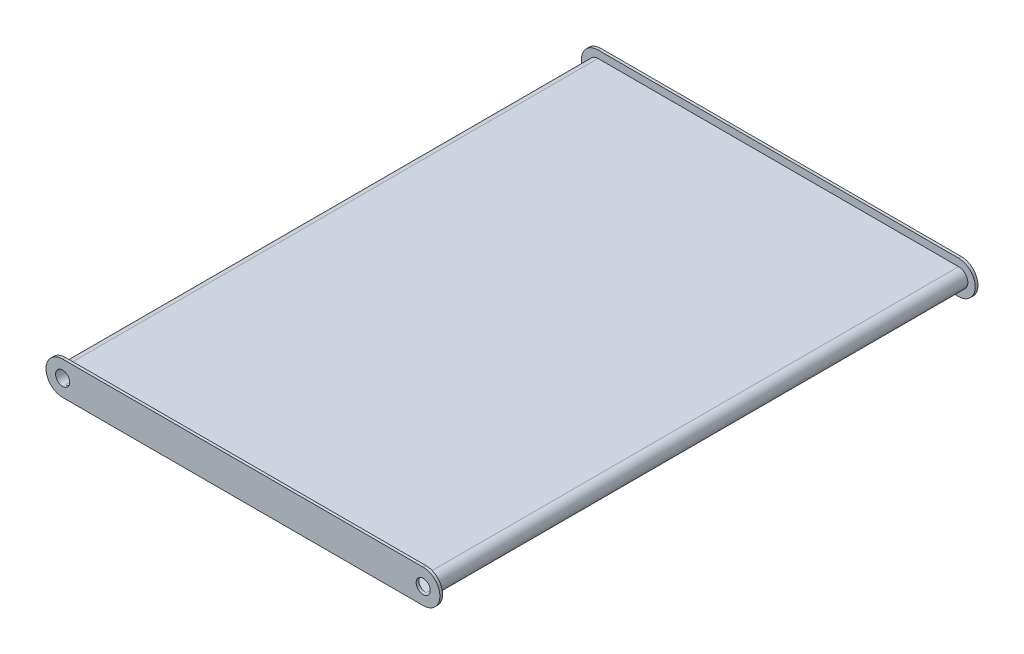
SolidWorks part; units mm, degrees
material "AISI 4130 Steel, annealed at 865C"
ref_plane "Front Plane" through (0, 0, 0) normal (0, 0, 1) x (1, 0, 0)
ref_plane "Top Plane" through (0, 0, 0) normal (0, 1, 0) x (1, 0, 0)
ref_plane "Right Plane" through (0, 0, 0) normal (1, 0, 0) x (0, 0, -1)
sketch "Sketch1" plane through (0, 0, 0) normal (0, 0, 1) x (1, 0, 0)
  line L0 (-324.9668, 0) -> (324.9668, 0) construction
  line L1 (-324.9668, 12.7) -> (324.9668, 12.7)
  line L2 (-324.9668, -12.7) -> (324.9668, -12.7)
  line L3 (-324.9668, 16.7) -> (324.9668, 16.7)
  line L4 (-324.9668, -16.7) -> (324.9668, -16.7)
  arc A0 (-324.9668, 12.7) -> (-324.9668, -12.7) centre (-324.9668, 0) ccw
  arc A1 (324.9668, -12.7) -> (324.9668, 12.7) centre (324.9668, 0) ccw
  arc A2 (324.9668, -16.7) -> (324.9668, 16.7) centre (324.9668, 0) ccw
  arc A3 (-324.9668, 16.7) -> (-324.9668, -16.7) centre (-324.9668, 0) ccw
  point P3 (0, 0)
  dimension "D2" = 12.7
  dimension "D1" = 649.9336
  dimension "D3" = 4
extrude "Boss-Extrude1" add sketch "Sketch1" along normal blind 960
sketch "Sketch2" plane through (0, 0, 960) normal (0, 0, 1) x (1, 0, 0)
  line L0 (-324.9668, 0) -> (324.9668, 0) construction
  line L1 (-324.9668, 30) -> (324.9668, 30)
  line L2 (-324.9668, -16.7) -> (324.9668, -16.7)
  line L3 (324.9668, 16.7) -> (-324.9668, 16.7)
  line L5 (324.9668, 16.7) -> (-324.9668, 16.7)
  line L6 (-324.9668, -30) -> (324.9668, -30)
  arc A0 (-324.9668, 30) -> (-324.9668, -30) centre (-324.9668, 0) ccw
  arc A1 (324.9668, -30) -> (324.9668, 30) centre (324.9668, 0) ccw
  arc A2 (-324.9668, 16.7) -> (-324.9668, -16.7) centre (-324.9668, 0) ccw
  arc A3 (324.9668, -16.7) -> (324.9668, 16.7) centre (324.9668, 0) ccw
  circle A6 centre (324.9668, 0) radius 12.7
  circle A7 centre (-324.9668, 0) radius 12.7
  point P0 (0, 0)
  dimension "D2" = 30
  dimension "D3" = 25.4
  dimension "D4" = 25.4
  dimension "D1" = 0
extrude "Boss-Extrude2" add sketch "Sketch2" along normal blind 5
ref_plane "Plane1" through (0, 0, 480) normal (0, 0, 1) x (1, 0, 0)
mirror "Mirror1" about plane through (0, 0, 480) normal (0, 0, 1) of "Boss-Extrude2"
sketch "Sketch3" plane through (0, 0, 480) normal (0, 0, 1) x (1, 0, 0)
  line L0 (-324.9668, 0) -> (324.9668, 0) construction
  line L1 (-324.9668, 21.7) -> (324.9668, 21.7)
  line L2 (-324.9668, -21.7) -> (324.9668, -21.7)
  line L4 (324.9668, 16.7) -> (-324.9668, 16.7) construction
  arc A0 (-324.9668, 21.7) -> (-324.9668, -21.7) centre (-324.9668, 0) ccw
  arc A1 (324.9668, -21.7) -> (324.9668, 21.7) centre (324.9668, 0) ccw
  point P4 (0, 0)
  dimension "D1" = 5
sketch "Sketch4" plane through (0, 0, 0) normal (0, 0, 1) x (1, 0, 0)
  line L0 (-324.9668, 0) -> (324.9668, 0) construction
  line L1 (-324.9668, 196.7) -> (324.9668, 196.7)
  line L2 (-324.9668, -196.7) -> (324.9668, -196.7)
  line L3 (324.9668, 16.7) -> (-324.9668, 16.7) construction
  arc A0 (-324.9668, 196.7) -> (-324.9668, -196.7) centre (-324.9668, 0) ccw
  arc A1 (324.9668, -196.7) -> (324.9668, 196.7) centre (324.9668, 0) ccw
  point P4 (0, 0)
  dimension "D1" = 180
